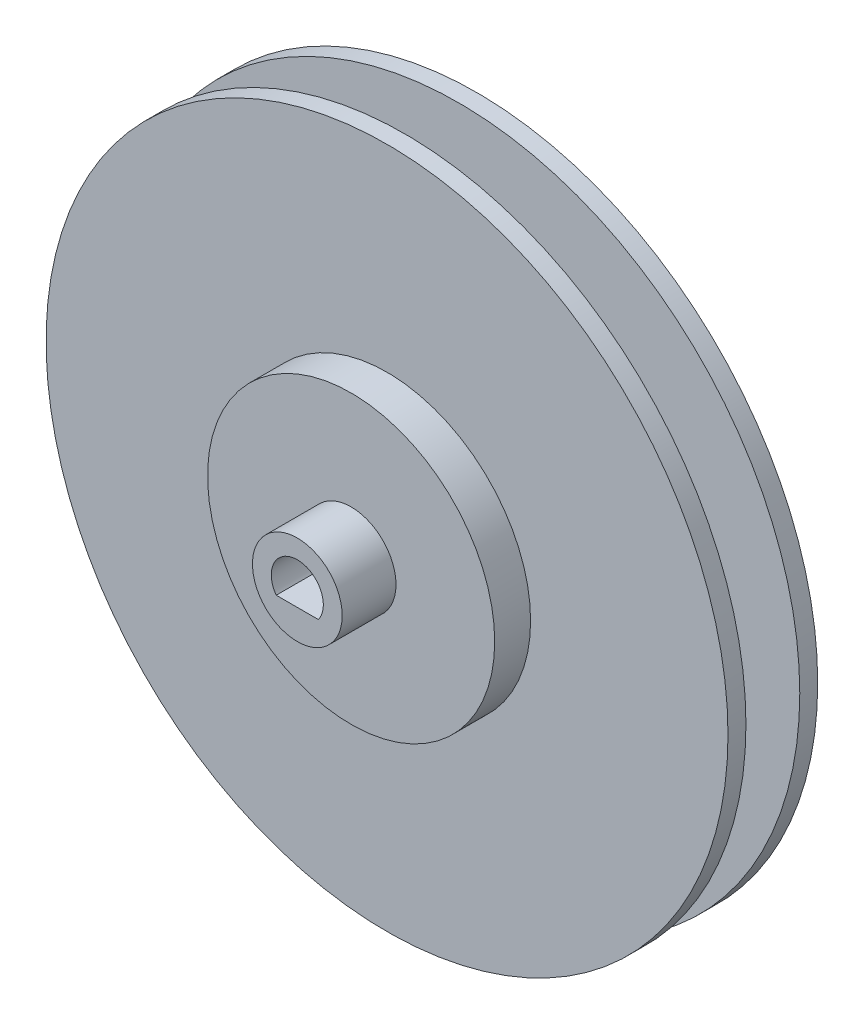
SolidWorks part; units mm, degrees
ref_plane "前视基准面" through (0, 0, 0) normal (0, 0, 1) x (1, 0, 0)
ref_plane "上视基准面" through (0, 0, 0) normal (0, 1, 0) x (1, 0, 0)
ref_plane "右视基准面" through (0, 0, 0) normal (1, 0, 0) x (0, 0, -1)
ref_axis "转轴" through (0, 0, 1.65) along (0, 0, -1)
sketch "草图1" plane through (0, 0, 0) normal (1, 0, 0) x (0, 0, -1)
  line L0 (0, 24.2) -> (0, -24.2) construction
  line L1 (-1.5, 6) -> (1.5, 6)
  line L2 (-1.5, 6) -> (-1.5, 7)
  line L3 (-1.5, 7) -> (1.5, 7)
  line L4 (1.5, 6) -> (1.5, 7)
  line L5 (-1.5, 6) -> (1.5, 7) construction
  line L6 (-1.5, 7) -> (1.5, 6) construction
  line L7 (-1.5, 19) -> (-2.5, 19)
  line L8 (1.5, 6) -> (2.5, 6)
  line L9 (1.5, 6) -> (1.5, 19)
  line L10 (1.5, 19) -> (2.5, 19)
  line L11 (2.5, 6) -> (2.5, 19)
  line L12 (-2.5, 6) -> (-2.5, 19)
  line L13 (-1.5, 6) -> (-2.5, 6)
  line L14 (-1.5, 6) -> (-1.5, 19)
  point P0 (0, 6.5)
  dimension "D1" = 6
  dimension "D2" = 1
  dimension "D3" = 3
  dimension "D4" = 1
  dimension "D5" = 12
revolve "主体" add sketch "草图1" angle 360 about axis through (0, 0, 1.65) along (0, 0, -1)
sketch "草图3" plane through (0, 0, 0) normal (0, 1, 0) x (1, 0, 0)
  line L5 (-13.2, 0) -> (13.2, 0) construction
  line L6 (-4.8904, 1.2) -> (-5.9904, 1.2)
  line L11 (-4.8904, 1.2) -> (-4.8904, -1.2)
  line L12 (-4.8904, -1.2) -> (-5.9904, -1.2)
  line L13 (-5.9904, 1.2) -> (-5.9904, -1.2)
  line L14 (-4.8904, 1.2) -> (-5.9904, -1.2) construction
  line L15 (-4.8904, -1.2) -> (-5.9904, 1.2) construction
  point P0 (-5.4404, 0)
  dimension "D1" = 2.4
  dimension "D2" = 1.1
extrude "穿线孔" cut sketch "草图3" against normal up to next from surface
sketch "草图4" plane through (0, 0, 2.5) normal (0, 0, 1) x (1, 0, 0)
  circle A0 centre (0, 0) radius 8
  circle A1 centre (0, 0) radius 6 construction
  dimension "D1" = 2
extrude "凸台-拉伸1" add sketch "草图4" along normal blind 2
sketch "草图5" plane through (0, 0, 4.5) normal (0, 0, 1) x (1, 0, 0)
  circle A0 centre (0, 0) radius 2.5
  dimension "D1" = 5
extrude "凸台-拉伸2" add sketch "草图5" along normal blind 3
sketch "草图6" plane through (0, 0, 7.5) normal (0, 0, 1) x (1, 0, 0)
  line L0 (1.1747, -0.85) -> (-1.1747, -0.85)
  line L1 (5.5, 0) -> (-5.5, 0) construction
  line L2 (4.5515, 1.45) -> (3.6882, 1.45) construction
  circle A0 centre (0, 0) radius 1.45
  dimension "D1" = 2.9
  dimension "D2" = 2.3
extrude "切除-拉伸2" cut sketch "草图6" against normal up to next contours L0 A0
